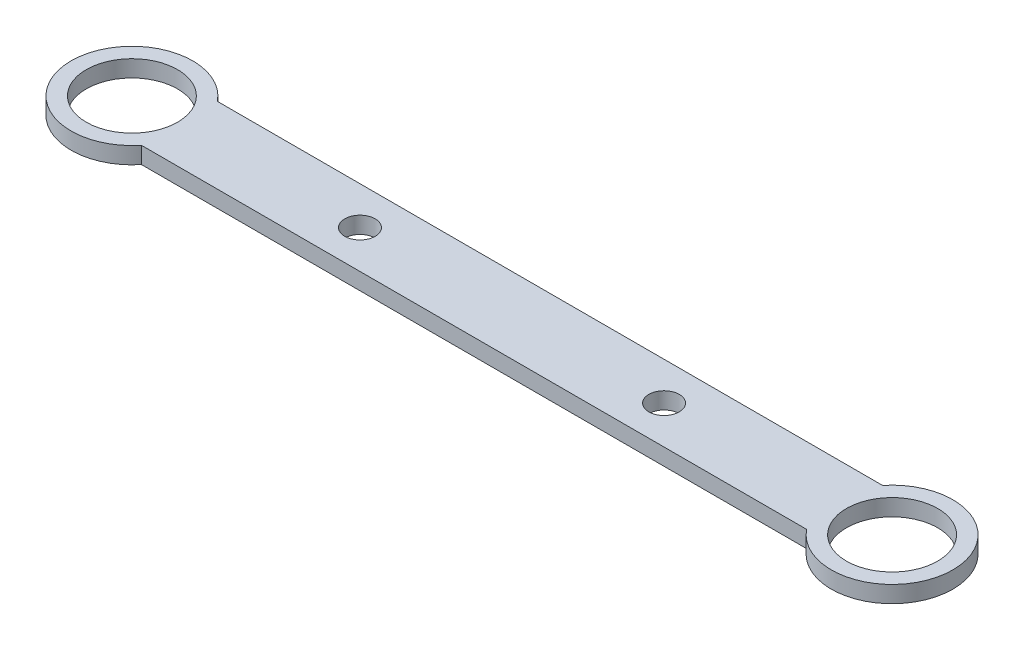
SolidWorks part; units mm, degrees
other "标注1"
sketch "草图3" plane through (-22.25, 4, -10) normal (-0.231, 0.6469, -0.7268) x (-0.9696, -0.2151, 0.1167)
ref_plane "前视基准面" through (0, 0, 0) normal (0, 0, 1) x (1, 0, 0)
ref_plane "上视基准面" through (0, 0, 0) normal (0, 1, 0) x (1, 0, 0)
ref_plane "右视基准面" through (0, 0, 0) normal (1, 0, 0) x (0, 0, -1)
other "Configuration Table"
sketch "草图4" plane through (0, 0, 0) normal (0, 1, 0) x (1, 0, 0)
  line L1 (3.1225, 2.5) -> (46.8775, 2.5)
  line L2 (3.1225, 2.5) -> (3.1225, -2.5)
  line L3 (3.1225, -2.5) -> (46.8775, -2.5)
  line L4 (46.8775, 2.5) -> (46.8775, -2.5)
  circle A0 centre (0, 0) radius 4
  circle A2 centre (0, 0) radius 3
  circle A3 centre (50, 0) radius 4
  circle A4 centre (50, 0) radius 3
  circle A5 centre (15, 0) radius 1
  circle A6 centre (35, 0) radius 1
  dimension "D1" = 8
  dimension "D2" = 50
  dimension "D3" = 6
  dimension "D5" = 2
  dimension "D4" = 5
  dimension "D6" = 15
  dimension "D7" = 15
extrude "凸台-拉伸1" add sketch "草图4" along normal blind 1.1
